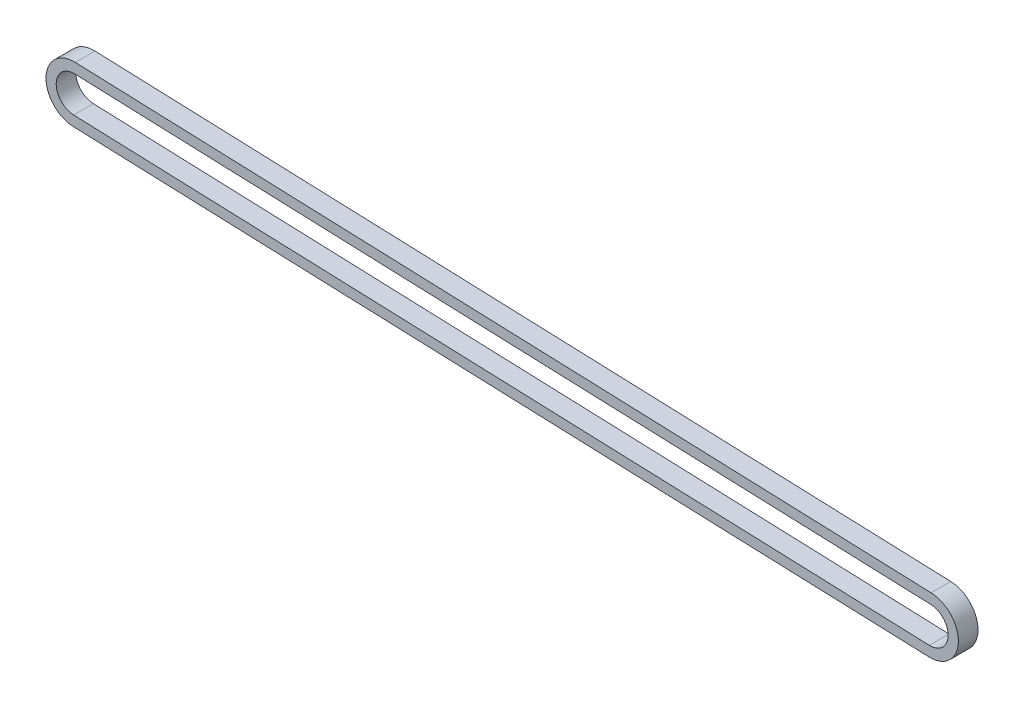
SolidWorks part; units mm, degrees
ref_plane "Front Plane" through (0, 0, 0) normal (0, 0, 1) x (1, 0, 0)
ref_plane "Top Plane" through (0, 0, 0) normal (0, 1, 0) x (1, 0, 0)
ref_plane "Right Plane" through (0, 0, 0) normal (1, 0, 0) x (0, 0, -1)
sketch "Sketch1" plane through (0, 0, 0) normal (0, 0, 1) x (1, 0, 0)
  line L0 (-138.2833, 2.161) -> (-0.1073, -2.919)
  line L1 (0.1073, 2.919) -> (-138.0687, 7.999)
  line L2 (0.168, 4.5689) -> (-138.008, 9.6489)
  line L3 (-138.344, 0.5111) -> (-0.168, -4.5689)
  circle A0 centre (0, 0) radius 2.921 construction
  circle A1 centre (-138.176, 5.08) radius 2.921 construction
  arc A2 (-0.1073, -2.919) -> (0.1073, 2.919) centre (0, 0) ccw
  arc A3 (-138.0687, 7.999) -> (-138.2833, 2.161) centre (-138.176, 5.08) ccw
  arc A4 (-138.008, 9.6489) -> (-138.344, 0.5111) centre (-138.176, 5.08) ccw
  arc A5 (-0.168, -4.5689) -> (0.168, 4.5689) centre (0, 0) ccw
  dimension "D1" = 5.842
  dimension "D2" = 5.842
  dimension "D5" = 294.8919
  dimension "D7" = 305.2654
  dimension "D3" = 5.08
  dimension "D4" = 138.176
  dimension "D6" = 1.651
extrude "Boss-Extrude1" add sketch "Sketch1" along normal blind 3.175
